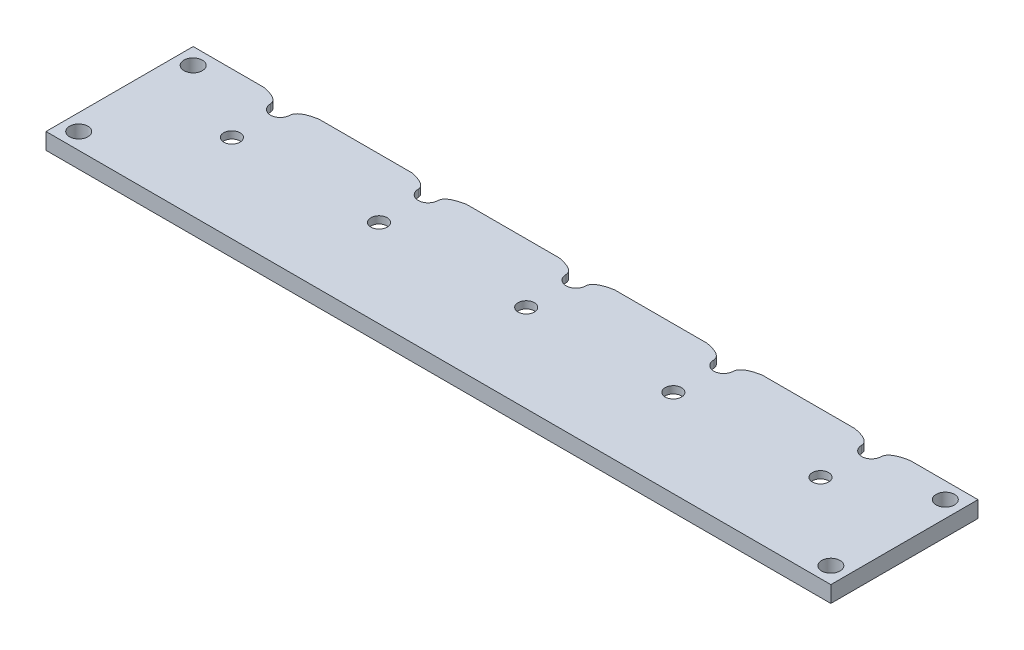
SolidWorks part; units mm, degrees
ref_plane "Front Plane" through (0, 0, 0) normal (0, 0, 1) x (1, 0, 0)
ref_plane "Top Plane" through (0, 0, 0) normal (0, 1, 0) x (1, 0, 0)
ref_plane "Right Plane" through (0, 0, 0) normal (1, 0, 0) x (0, 0, -1)
sketch "Sketch1" plane through (0, 0, 0) normal (0, 1, 0) x (1, 0, 0)
  line L0 (19.05, 28.3464) -> (19.05, 24.5364)
  line L1 (0, 0) -> (152.4, 0)
  line L2 (0, 0) -> (0, 28.575)
  line L3 (0, 28.575) -> (13.7291, 28.575)
  line L4 (152.4, 0) -> (152.4, 28.575)
  line L5 (24.371, 28.575) -> (42.431, 28.575)
  line L6 (53.073, 28.575) -> (71.133, 28.575)
  line L7 (81.775, 28.575) -> (99.835, 28.575)
  line L8 (110.477, 28.575) -> (128.537, 28.575)
  line L9 (139.179, 28.575) -> (152.4, 28.575)
  circle A0 centre (19.05, 17.0434) radius 1.5875
  circle A1 centre (47.625, 17.0434) radius 1.5875
  circle A2 centre (76.2, 17.0434) radius 1.5875
  circle A3 centre (104.775, 17.0434) radius 1.5875
  circle A4 centre (133.35, 17.0434) radius 1.5875
  arc A5 (17.145, 26.4414) -> (20.955, 26.4414) centre (19.05, 26.4414) ccw
  arc A16 (45.847, 26.4414) -> (49.657, 26.4414) centre (47.752, 26.4414) ccw
  arc A17 (74.549, 26.4414) -> (78.359, 26.4414) centre (76.454, 26.4414) ccw
  arc A18 (103.251, 26.4414) -> (107.061, 26.4414) centre (105.156, 26.4414) ccw
  arc A19 (131.953, 26.4414) -> (135.763, 26.4414) centre (133.858, 26.4414) ccw
  spline S0 degree 2 poles (13.729, 28.575) (17.0425, 27.9407) (17.145, 26.4414) knots 0 0 0 0.606076 0.606076 0.606076
  spline S1 degree 2 poles (24.371, 28.575) (21.0575, 27.9407) (20.955, 26.4414) knots 0 0 0 0.606076 0.606076 0.606076
  spline S2 degree 2 poles (42.431, 28.575) (45.7445, 27.9407) (45.847, 26.4414) knots 0 0 0 0.606076 0.606076 0.606076
  spline S3 degree 2 poles (53.073, 28.575) (49.7595, 27.9407) (49.657, 26.4414) knots 0 0 0 0.606076 0.606076 0.606076
  spline S4 degree 2 poles (71.133, 28.575) (74.4465, 27.9407) (74.549, 26.4414) knots 0 0 0 0.606076 0.606076 0.606076
  spline S5 degree 2 poles (81.775, 28.575) (78.4615, 27.9407) (78.359, 26.4414) knots 0 0 0 0.606076 0.606076 0.606076
  spline S6 degree 2 poles (99.835, 28.575) (103.1485, 27.9407) (103.251, 26.4414) knots 0 0 0 0.606076 0.606076 0.606076
  spline S7 degree 2 poles (110.477, 28.575) (107.1635, 27.9407) (107.061, 26.4414) knots 0 0 0 0.606076 0.606076 0.606076
  spline S8 degree 2 poles (128.537, 28.575) (131.8505, 27.9407) (131.953, 26.4414) knots 0 0 0 0.606076 0.606076 0.606076
  spline S9 degree 2 poles (139.179, 28.575) (135.8655, 27.9407) (135.763, 26.4414) knots 0 0 0 0.606076 0.606076 0.606076
  dimension "D8" = 3.175
  dimension "D9" = 3.175
  dimension "D10" = 3.175
  dimension "D11" = 3.175
  dimension "D12" = 3.175
  dimension "D14" = 3.81
  dimension "D17" = 0
  dimension "D18" = 0
  dimension "D19" = 0
  dimension "D20" = 0
  dimension "D1" = 28.575
  dimension "D2" = 19.05
  dimension "D3" = 19.05
  dimension "D4" = 28.575
  dimension "D5" = 28.575
  dimension "D6" = 28.575
  dimension "D7" = 28.575
  dimension "D13" = 11.5316
  dimension "D15" = 9.398
  dimension "D16" = 5
extrude "Boss-Extrude1" add sketch "Sketch1" along normal blind 3.175 contours L9 S9 A19 S8 L8 S7 A18 S6 L7 S5 A17 S4 L6 S3 A16 S2 L5 S1 A5 S0 L3 L2 L1 L4 A0 A1 A2 A3 A4
sketch "Sketch2" plane through (0, 0, 0) normal (0, -1, 0) x (1, 0, 0)
  circle A0 centre (19.05, -17.0434) radius 13.97
  circle A1 centre (47.625, -17.0434) radius 13.97
  circle A2 centre (76.2, -17.0434) radius 13.97
  circle A3 centre (104.775, -17.0434) radius 13.97
  circle A4 centre (133.35, -17.0434) radius 13.97
  dimension "D1" = 27.94
extrude "Cut-Extrude1" cut sketch "Sketch2" against normal blind 1.778
hole_wizard "9/64 (0.14063) Diameter Hole1" positions "Sketch5" profile "Sketch7" hole size "9/64" standard "ANSI Inch" end condition up to next
sketch "Sketch5" plane through (0, 3.175, 0) normal (0, 1, 0) x (1, 0, 0)
  line L0 (0, 0) -> (0, 28.575) construction
  line L1 (0, 28.575) -> (13.729, 28.575) construction
  line L2 (0, 0) -> (152.4, 0) construction
  line L3 (139.179, 28.575) -> (152.4, 28.575) construction
  line L4 (152.4, 0) -> (152.4, 28.575) construction
  point P0 (3.175, 25.4)
  point P2 (3.175, 3.175)
  point P4 (149.225, 3.175)
  point P6 (149.225, 25.4)
  point P17 (3.175, 2.991)
  dimension "D1" = 3.175
  dimension "D2" = 3.175
  dimension "D3" = 3.175
  dimension "D4" = 3.175
  dimension "D5" = 3.175
  dimension "D6" = 3.175
  dimension "D7" = 3.175
  dimension "D8" = 3.175
sketch "Sketch7" plane through (3.175, 3.175, -25.4) normal (1, 0, 0) x (0, 0, 1)
  line L0 (0, 0) -> (0, 3.175)
  line L1 (0, 3.175) -> (1.786, 3.175)
  line L2 (1.786, 3.175) -> (1.786, 0)
  line L5 (1.786, 0) -> (0, 0)
  line L11 (0, -6.35) -> (0, 107.95) construction
  dimension "Thru Hole Dia." = 3.572
  dimension "Thru Hole Depth" = 3.175
